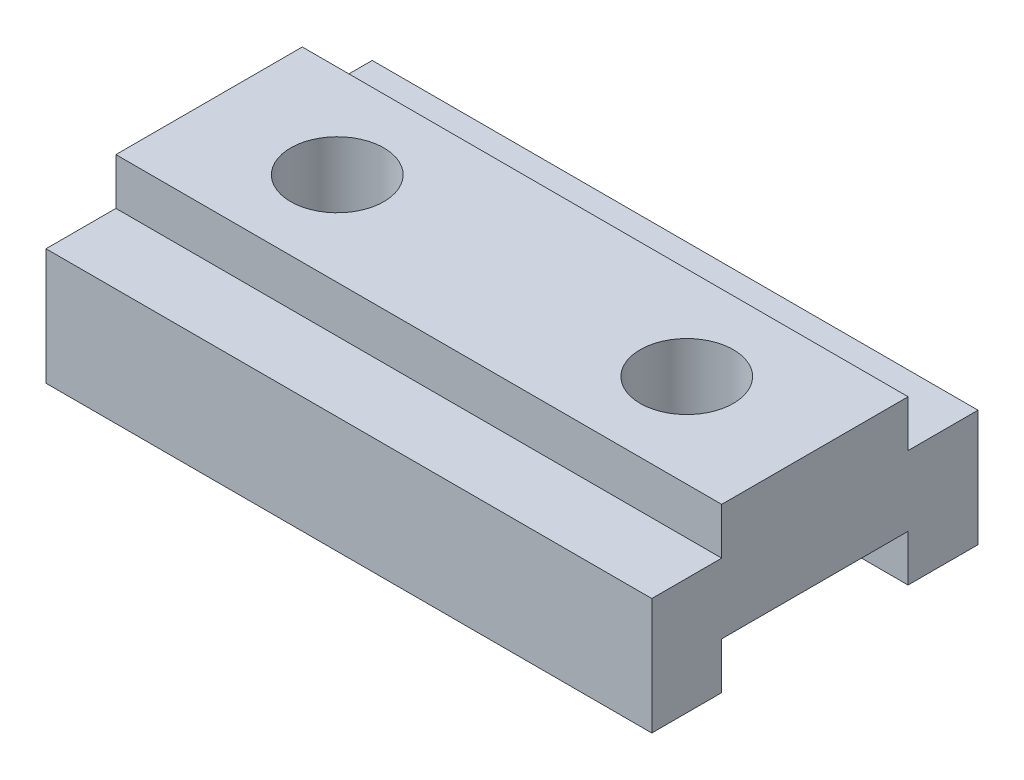
SolidWorks part; units mm, degrees
ref_plane "Front Plane" through (0, 0, 0) normal (0, 0, 1) x (1, 0, 0)
ref_plane "Top Plane" through (0, 0, 0) normal (0, 1, 0) x (1, 0, 0)
ref_plane "Right Plane" through (0, 0, 0) normal (1, 0, 0) x (0, 0, -1)
sketch "Sketch1" plane through (0, 0, 0) normal (1, 0, 0) x (0, 0, -1)
  line L0 (19.05, 0) -> (19.05, 12.7)
  line L1 (0, 0) -> (19.05, 0)
  line L2 (0, 0) -> (0, 31.75)
  line L3 (19.05, 44.45) -> (69.85, 44.45)
  line L4 (88.9, 0) -> (88.9, 31.75)
  line L5 (19.05, 12.7) -> (69.85, 12.7)
  line L6 (69.85, 12.7) -> (69.85, 0)
  line L7 (0, 31.75) -> (19.05, 31.75)
  line L8 (19.05, 31.75) -> (19.05, 44.45)
  line L9 (69.85, 44.45) -> (69.85, 31.75)
  line L10 (69.85, 31.75) -> (88.9, 31.75)
  line L11 (69.85, 0) -> (88.9, 0)
  dimension "D1" = 44.45
  dimension "D2" = 31.75
  dimension "D3" = 88.9
  dimension "D4" = 50.8
  dimension "D5" = 12.7
  dimension "D6" = 19.05
extrude "Boss-Extrude1" add sketch "Sketch1" against normal blind 165.1
sketch "Sketch3" plane through (0, 44.45, 0) normal (0, 1, 0) x (1, 0, 0)
  line L0 (-165.1, 19.05) -> (0, 19.05) construction
  line L1 (-165.1, 69.85) -> (-165.1, 19.05) construction
  circle A0 centre (-130.175, 44.45) radius 12.7
  circle A1 centre (-34.925, 44.45) radius 12.7
  dimension "D2" = 25.4
  dimension "D3" = 34.925
  dimension "D1" = 25.4
  dimension "D4" = 130.175
extrude "Cut-Extrude1" cut sketch "Sketch3" against normal through all
